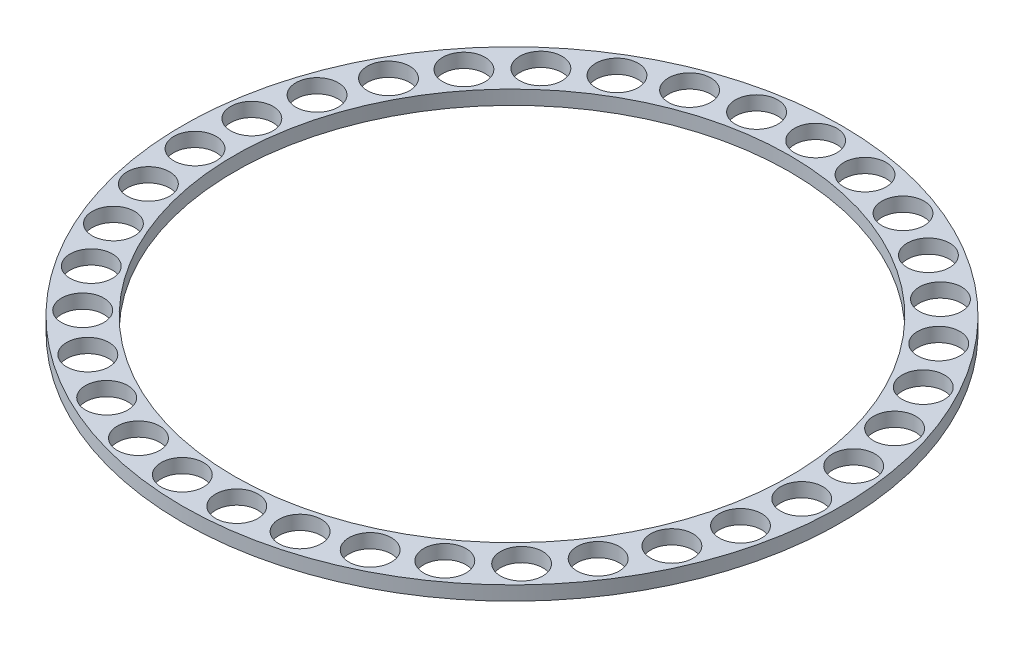
SolidWorks part; units mm, degrees
ref_plane "Alzado" through (0, 0, 0) normal (0, 0, 1) x (1, 0, 0)
ref_plane "Planta" through (0, 0, 0) normal (0, 1, 0) x (1, 0, 0)
ref_plane "Vista lateral" through (0, 0, 0) normal (1, 0, 0) x (0, 0, -1)
sketch "Croquis1" plane through (0, 0, 0) normal (0, 1, 0) x (1, 0, 0)
  circle A1 centre (0, 0) radius 70
  circle A2 centre (0, 0) radius 59
  dimension "D2" = 140
  dimension "D3" = 118
extrude "Saliente-Extruir1" add sketch "Croquis1" against normal mid plane 3
sketch "Croquis3" plane through (0, -1.5, 0) normal (0, -1, 0) x (-1, 0, 0)
  line L0 (0, 0) -> (0, 70)
  line L1 (0, 70) -> (0, 64.5)
  circle A0 centre (0, 0) radius 70 construction
  circle A1 centre (0, 64.5) radius 4.5
  dimension "D2" = 9
  dimension "D1" = 5.5
extrude "Cortar-Extruir1" cut sketch "Croquis3" against normal blind 5 contours A1
pattern_circular "MatrizC1" count 35 over 360 about axis through (0, 0, 0) along (0, 1, 0) of "Cortar-Extruir1"
